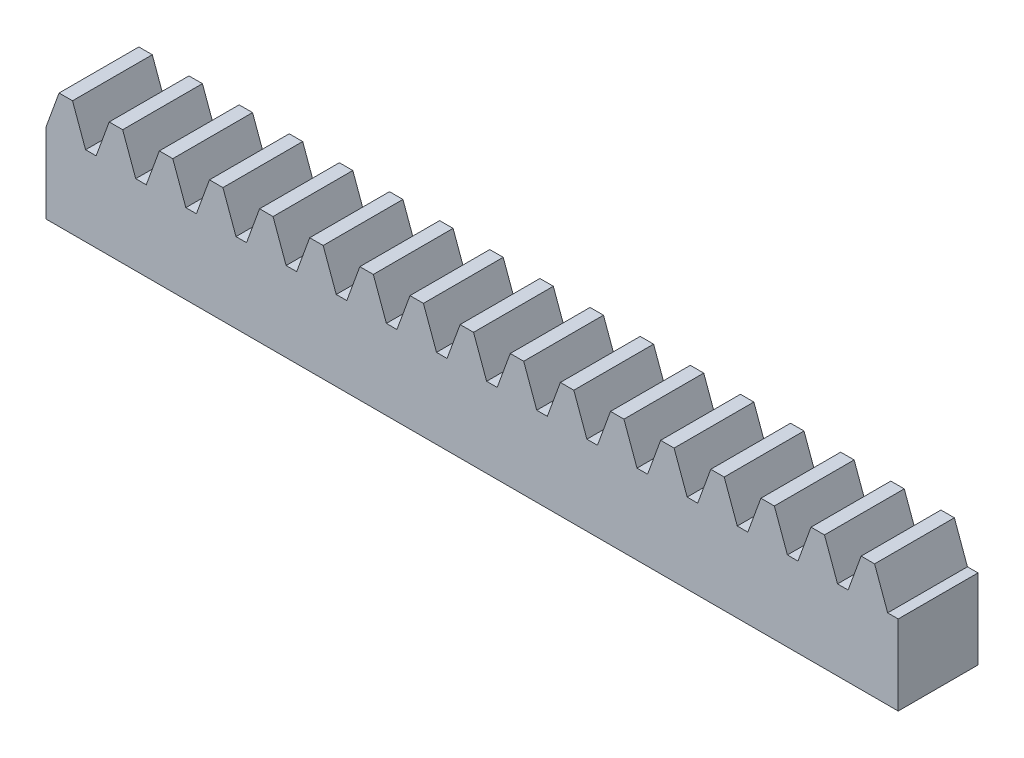
SolidWorks part; units mm, degrees
ref_plane "前视基准面" through (0, 0, 0) normal (0, 0, 1) x (1, 0, 0)
ref_plane "上视基准面" through (0, 0, 0) normal (0, 1, 0) x (1, 0, 0)
ref_plane "右视基准面" through (0, 0, 0) normal (1, 0, 0) x (0, 0, -1)
sketch "草图1" plane through (0, 0, 0) normal (0, 0, 1) x (1, 0, 0)
  line L1 (0, 0) -> (106.8142, 0)
  line L2 (0, 0) -> (0, -10)
  line L3 (0, -10) -> (106.8142, -10)
  line L4 (106.8142, 0) -> (106.8142, -10)
  dimension "D1" = 10
  dimension "L" = 106.8142
extrude "拉伸1" add sketch "草图1" along normal blind 10
sketch "草图2" plane through (0, 0, 10) normal (0, 0, 1) x (1, 0, 0)
  line L0 (0, 0) -> (1.6379, 4.5)
  line L1 (1.6379, 4.5) -> (3.3236, 4.5)
  line L2 (3.3236, 4.5) -> (4.9614, 0)
  line L3 (106.8142, 0) -> (0, 0) construction
  line L4 (0, 0) -> (4.9614, 0)
  line L5 (0.9099, 2.5) -> (4.0515, 2.5) construction
  dimension "D2" = 70
  dimension "alpha" = 110
  dimension "ha" = 2
  dimension "hf" = 2.5
  dimension "S" = 3.1416
extrude "拉伸2" add sketch "草图2" against normal up to surface (10 mm away) up to face at (53.4071, -5, 0)
pattern_linear "阵列(线性)1" count 17 spacing 6.2832 along (1, 0, 0) of "拉伸2"
equation "\"d\"=\"S@草图2\" * 2"
equation "\"z\"= int(  \"L@草图1\" / (  \"S@草图2\" * 2 ) + 0.5 )"
